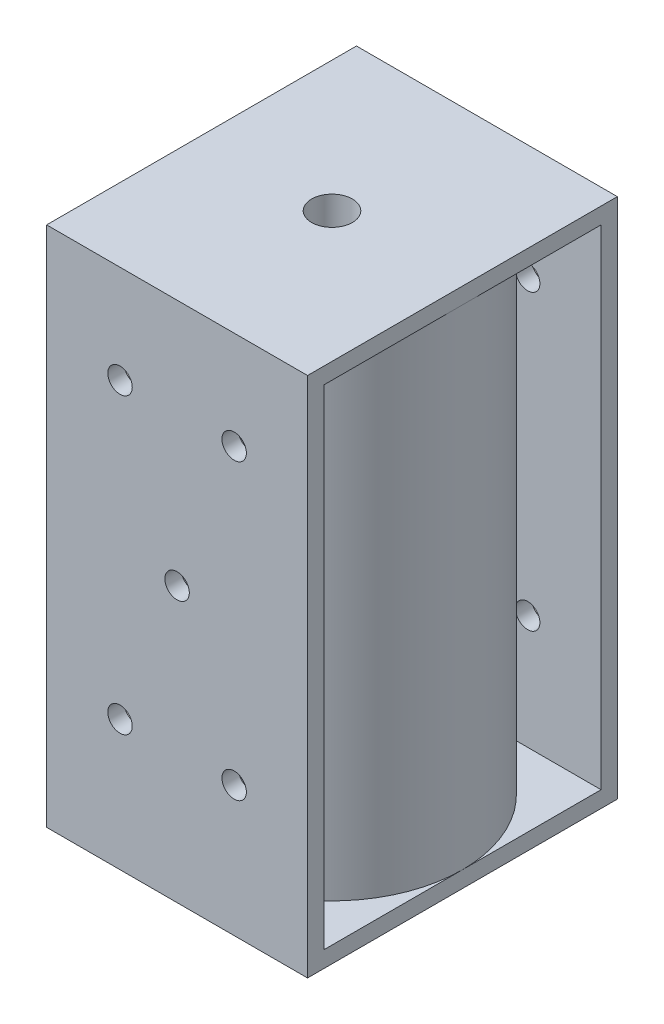
SolidWorks part; units mm, degrees
ref_plane "Front Plane" through (0, 0, 0) normal (0, 0, 1) x (1, 0, 0)
ref_plane "Top Plane" through (0, 0, 0) normal (0, 1, 0) x (1, 0, 0)
ref_plane "Right Plane" through (0, 0, 0) normal (1, 0, 0) x (0, 0, -1)
sketch "Sketch1" plane through (0, 0, 0) normal (1, 0, 0) x (0, 0, -1)
  line L0 (-17, -30) -> (-17, 30)
  line L1 (-19, -32) -> (19, -32)
  line L2 (-19, -32) -> (-19, 32)
  line L3 (-19, 32) -> (19, 32)
  line L4 (19, -32) -> (19, 32)
  line L5 (-19, -32) -> (19, 32) construction
  line L6 (-19, 32) -> (19, -32) construction
  line L7 (-17, 30) -> (17, 30)
  line L8 (17, -30) -> (17, 30)
  line L9 (-17, -30) -> (17, -30)
  point P0 (0, 0)
  dimension "D1" = 38
  dimension "D2" = 64
  dimension "D3" = 2
extrude "Boss-Extrude1" add sketch "Sketch1" along normal blind 32
sketch "Sketch2" plane through (0, 0, 19) normal (0, 0, 1) x (1, 0, 0)
  line L0 (0, 20) -> (32, 20) construction
  line L1 (0, 32) -> (0, -32) construction
  line L2 (32, 32) -> (32, -32) construction
  line L3 (32, 32) -> (0, 32) construction
  line L4 (0, -16) -> (32, -16) construction
  line L5 (9, 32) -> (9, -32) construction
  line L6 (32, -32) -> (0, -32) construction
  line L7 (23, 32) -> (23, -32) construction
  line L8 (16, 32) -> (16, -32) construction
  circle A0 centre (9, 20) radius 1.5
  circle A1 centre (23, 20) radius 1.5
  circle A2 centre (16, 1.6635) radius 1.5
  circle A3 centre (9, -16) radius 1.5
  circle A4 centre (23, -16) radius 1.5
  point P29 (16, 32)
  dimension "D1" = 3
  dimension "D2" = 3
  dimension "D3" = 3
  dimension "D4" = 3
  dimension "D5" = 3
  dimension "D6" = 12
  dimension "D7" = 36
  dimension "D8" = 9
  dimension "D9" = 9
  dimension "D10" = 19
extrude "Cut-Extrude1" cut sketch "Sketch2" against normal through all
sketch "Sketch7" plane through (0, -30, 0) normal (0, 1, 0) x (1, 0, 0)
  line L0 (0, 17) -> (32, -17) construction
  line L1 (32, 17) -> (0, -17) construction
  circle A0 centre (16, 0) radius 16
  dimension "D1" = 32
extrude "Boss-Extrude3" add sketch "Sketch7" along normal up to next
sketch "Sketch8" plane through (0, 32, 0) normal (0, 1, 0) x (1, 0, 0)
  line L0 (32, 19) -> (0, -19) construction
  line L1 (0, 19) -> (32, -19) construction
  circle A0 centre (16, 0) radius 2.5
  dimension "D1" = 5
extrude "Cut-Extrude2" cut sketch "Sketch8" against normal through all
sketch "Sketch9" plane through (0, -32, 0) normal (0, -1, 0) x (1, 0, 0)
  circle A0 centre (16, 0) radius 6
  dimension "D1" = 12
extrude "Cut-Extrude3" cut sketch "Sketch9" against normal blind 40
